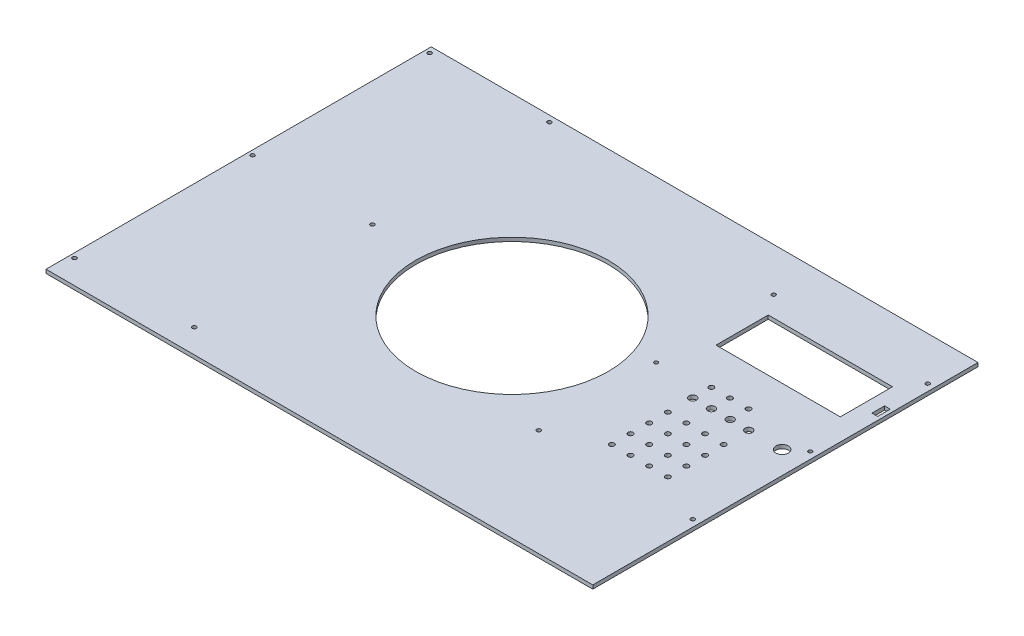
SolidWorks part; units mm, degrees
ref_plane "Front Plane" through (0, 0, 0) normal (0, 0, 1) x (1, 0, 0)
ref_plane "Top Plane" through (0, 0, 0) normal (0, 1, 0) x (1, 0, 0)
ref_plane "Right Plane" through (0, 0, 0) normal (1, 0, 0) x (0, 0, -1)
sketch "Sketch1" plane through (0, 0, 0) normal (0, 1, 0) x (1, 0, 0)
  line L0 (152.5, 25.5) -> (152.5, 139.9) construction
  line L1 (-220, 155) -> (220, 155)
  line L2 (-220, 155) -> (-220, -155)
  line L3 (-220, -155) -> (220, -155)
  line L4 (220, 155) -> (220, -155)
  line L5 (-220, 155) -> (220, -155) construction
  line L6 (-220, -155) -> (220, 155) construction
  line L11 (90.5, 120) -> (214.5, 120) construction
  line L12 (90.5, 120) -> (90.5, -69) construction
  line L13 (90.5, -69) -> (214.5, -69) construction
  line L14 (214.5, 120) -> (214.5, -69) construction
  line L15 (90.5, 120) -> (214.5, -69) construction
  line L16 (90.5, -69) -> (214.5, 120) construction
  line L17 (152.5, 25.5) -> (176.7267, 25.5) construction
  line L19 (102.5, 103.7) -> (202.5, 103.7)
  line L20 (102.5, 103.7) -> (102.5, 61.7)
  line L21 (102.5, 61.7) -> (202.5, 61.7)
  line L22 (202.5, 103.7) -> (202.5, 61.7)
  line L23 (102.5, 103.7) -> (202.5, 61.7) construction
  line L24 (102.5, 61.7) -> (202.5, 103.7) construction
  line L25 (212.6302, 87.191) -> (217.236, 87.191)
  line L26 (212.6302, 87.191) -> (212.6302, 76.991)
  line L27 (212.6302, 76.991) -> (217.236, 76.991)
  line L28 (217.236, 87.191) -> (217.236, 76.991)
  circle A0 centre (0, 0) radius 77.5
  circle A1 centre (-216.3, 150) radius 1.6
  circle A2 centre (-119.9, 150) radius 1.6
  circle A3 centre (-216.3, 7.5) radius 1.6
  circle A4 centre (-119.9, 7.5) radius 1.6
  circle A5 centre (-216.3, -135.76) radius 1.6
  circle A6 centre (-119.9, -135.76) radius 1.6
  circle A7 centre (214.5, 120) radius 1.6
  circle A8 centre (90.5, 120) radius 1.6
  circle A9 centre (214.5, -69) radius 1.6
  circle A10 centre (90.5, -69) radius 1.6
  circle A11 centre (130.003, 30.3821) radius 2
  circle A12 centre (145.003, 30.3821) radius 2
  circle A13 centre (160.003, 30.3821) radius 2
  circle A16 centre (130, 15.525) radius 3
  circle A17 centre (145, 15.525) radius 3
  circle A18 centre (160, 15.525) radius 3
  circle A19 centre (175, 15.525) radius 3
  circle A20 centre (201.84, 15.525) radius 5
  circle A21 centre (214.5, 25.525) radius 1.5
  circle A22 centre (90.5, 25.5) radius 1.5
  circle A23 centre (129.8571, -4.478) radius 2
  circle A24 centre (144.8571, -4.478) radius 2
  circle A25 centre (159.8571, -4.478) radius 2
  circle A26 centre (174.8571, -4.478) radius 2
  circle A27 centre (144.8571, -19.478) radius 2
  circle A28 centre (159.8571, -19.478) radius 2
  circle A29 centre (174.8571, -19.478) radius 2
  circle A30 centre (144.8571, -34.478) radius 2
  circle A31 centre (159.8571, -34.478) radius 2
  circle A32 centre (174.8571, -34.478) radius 2
  circle A33 centre (144.8571, -49.478) radius 2
  circle A34 centre (159.8571, -49.478) radius 2
  circle A35 centre (174.8571, -49.478) radius 2
  circle A36 centre (129.8571, -19.478) radius 2
  circle A37 centre (129.8571, -34.478) radius 2
  circle A38 centre (129.8571, -49.478) radius 2
  point P0 (0, 0)
  point P8 (152.5, 82.7)
  point P18 (152.5, 25.5)
  dimension "D3" = 155
  dimension "D4" = 3.2
  dimension "D7" = 96.4
  dimension "D10" = 3.2
  dimension "D18" = 6
  dimension "D20" = 10
  dimension "D21" = 3
  dimension "D22" = 3
  dimension "D23" = 4
  dimension "D1" = 310
  dimension "D2" = 440
  dimension "D5" = 3.7
  dimension "D6" = 5
  dimension "D11" = 35
  dimension "D12" = 5.5
  dimension "D13" = 124
  dimension "D14" = 189
  dimension "D15" = 42
  dimension "D16" = 100
  dimension "D17" = 36.2
  dimension "D19" = 4
  dimension "D8" = 2
  dimension "D9" = 2
  dimension "D24" = 4
  dimension "D25" = 4
extrude "Boss-Extrude1" add sketch "Sketch1" along normal mid plane 3
